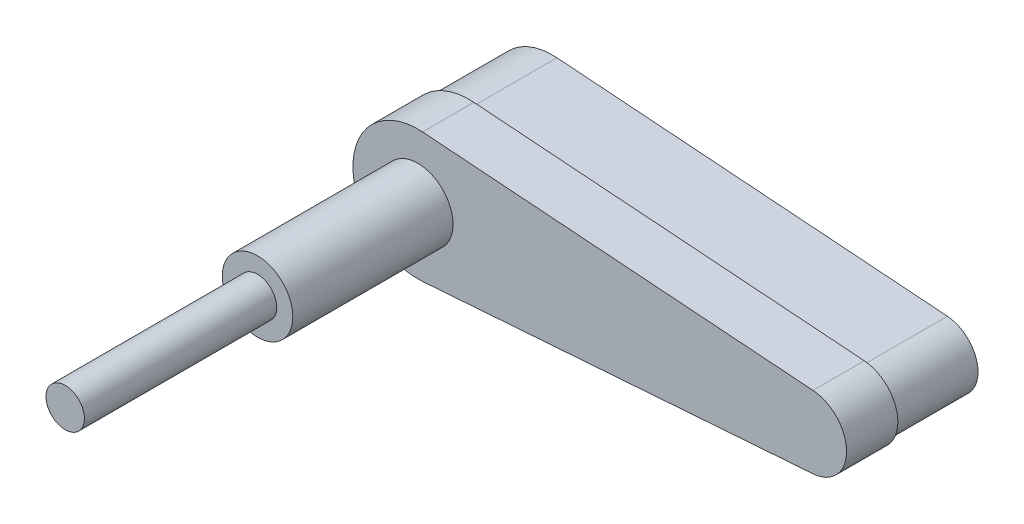
SolidWorks part; units mm, degrees
material "ABS"
ref_plane "Plan de face" through (0, 0, 0) normal (0, 0, 1) x (1, 0, 0)
ref_plane "Plan de dessus" through (0, 0, 0) normal (0, 1, 0) x (1, 0, 0)
ref_plane "Plan de droite" through (0, 0, 0) normal (1, 0, 0) x (0, 0, -1)
sketch "Esquisse1" plane through (0, 0, 0) normal (0, 0, 1) x (1, 0, 0)
  line L0 (0, 0) -> (76, 0) construction
  line L1 (10.3295, 9.6) -> (71.227, 5.1357)
  line L2 (10.3295, -9.6) -> (71.227, -5.1357)
  arc A0 (10.3295, 9.6) -> (10.3295, -9.6) centre (9.6258, 0) ccw
  arc A1 (71.227, 5.1357) -> (71.227, -5.1357) centre (70.8505, 0) cw
  dimension "D1" = 9.6
  dimension "D3" = 5.1357
extrude "Boss.-Extru.1" add sketch "Esquisse1" along normal blind 13
sketch "Esquisse3" plane through (0, 0, 13) normal (0, 0, 1) x (1, 0, 0)
  line L4 (71.2636, 5.6344) -> (10.3661, 10.0987)
  line L5 (10.3661, -10.0987) -> (71.2636, -5.6344)
  arc A0 (10.3295, 9.6) -> (10.3295, -9.6) centre (9.6258, 0) ccw construction
  arc A4 (10.3661, 10.0987) -> (10.3661, -10.0987) centre (9.6258, 0) ccw
  arc A5 (71.2636, -5.6344) -> (71.2636, 5.6344) centre (70.8505, 0) ccw
  point P3 (0, 0)
  dimension "D1" = 20.1973
  dimension "D2" = 11.2687
  dimension "D3" = 61.2248
  dimension "D4" = 9.6258
  dimension "D5" = 5.6344
extrude "Boss.-Extru.2" add sketch "Esquisse3" along normal blind 8
sketch "Esquisse4" plane through (0, 0, 21) normal (0, 0, 1) x (1, 0, 0)
  circle A0 centre (9.6258, 0) radius 5.5
  arc A1 (10.3661, 10.0987) -> (10.3661, -10.0987) centre (9.6258, 0) ccw construction
  dimension "D1" = 11
extrude "Boss.-Extru.3" add sketch "Esquisse4" along normal blind 55
sketch "Esquisse5" plane through (0, 0, 76) normal (0, 0, 1) x (1, 0, 0)
  circle A0 centre (9.6258, 0) radius 3
  circle A1 centre (9.6258, 0) radius 5.5 construction
  circle A2 centre (9.6258, 0) radius 5.5
  dimension "D1" = 6
extrude "Enlèv. mat.-Extru.1" cut sketch "Esquisse5" against normal blind 30
